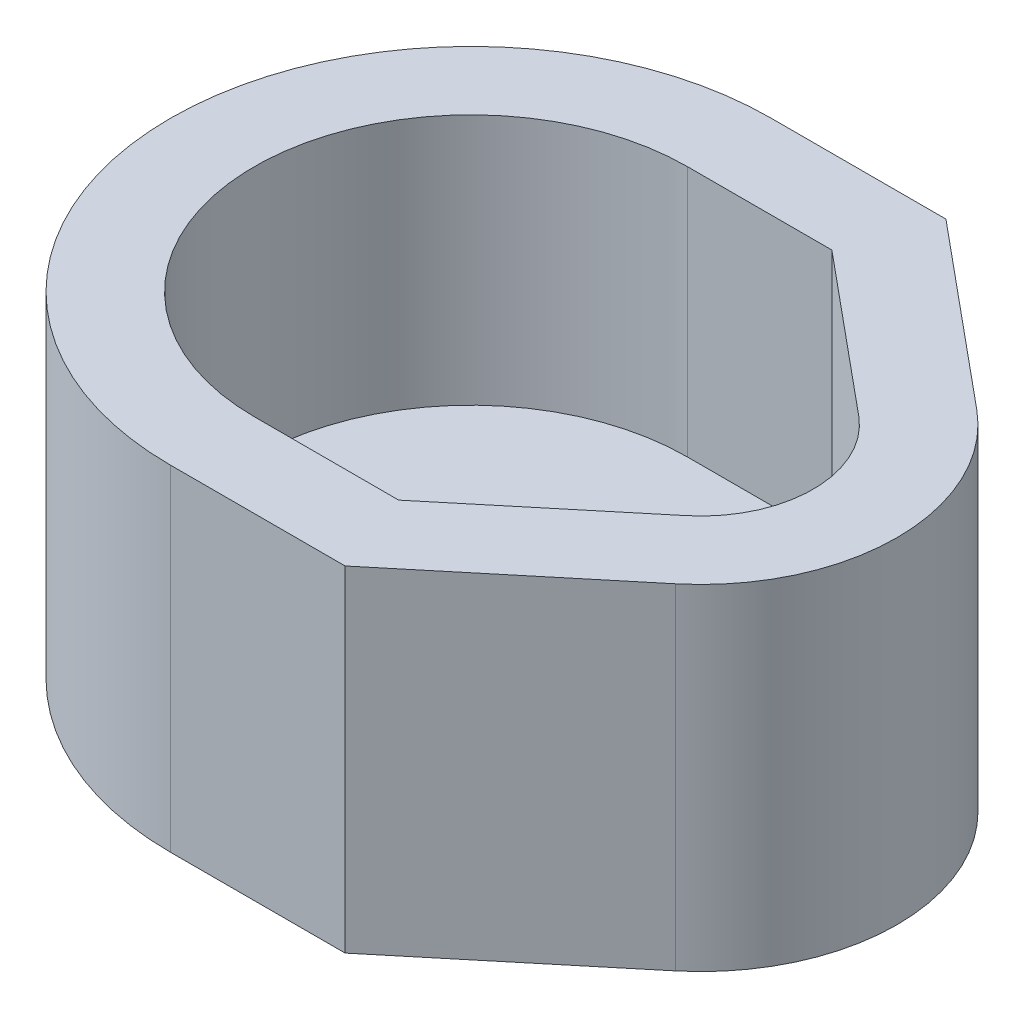
SolidWorks part; units mm, degrees
ref_plane "Front Plane" through (0, 0, 0) normal (0, 0, 1) x (1, 0, 0)
ref_plane "Top Plane" through (0, 0, 0) normal (0, 1, 0) x (1, 0, 0)
ref_plane "Right Plane" through (0, 0, 0) normal (1, 0, 0) x (0, 0, -1)
sketch "Sketch1" plane through (0, 0, 0) normal (0, 1, 0) x (1, 0, 0)
  line L9 (13.2334, 0) -> (26.9219, 11.3488)
  line L10 (26.9219, 34.168) -> (13.2334, 45.5168)
  line L12 (0, 0) -> (13.2334, 0)
  line L13 (0, 45.5168) -> (13.2334, 45.5168)
  arc A0 (26.9219, 11.3488) -> (26.9219, 34.168) centre (17.4625, 22.7584) ccw
  arc A1 (0, 45.5168) -> (0, 0) centre (0, 22.7584) ccw
  dimension "D1" = 22.7584
  dimension "D2" = 14.8209
  dimension "D3" = 13.2334
  dimension "D4" = 17.4625
extrude "Boss-Extrude1" add sketch "Sketch1" along normal blind 25.4
shell "Shell1" thickness 6.35
sketch "Sketch2" plane through (0, 6.35, 0) normal (0, 1, 0) x (1, 0, 0)
  circle A0 centre (0, 22.7584) radius 3.9815
  circle A1 centre (17.4625, 22.7584) radius 3.1877
  dimension "D1" = 7.9629
  dimension "D2" = 6.3754
extrude "Cut-Extrude1" cut sketch "Sketch2" against normal through all
equation "\"odpin\"= 0.417'OD of pinion gear, inches"
equation "\"pdpin\"= 0.375'pitch diameter of pinion, inches"
equation "\"odge\"= 1.042'od of big gear, inches"
equation "\"pdge\"= 1'pitch diameter gear, inches"
equation "\"wcent\"= ( ( \"pdpin\" + \"pdge\" ) / 2 )'length between centerline of shafts"
equation "\"clear\"= 1 / 8'clearance, per side"
equation "\"D1@Sketch1\"=(\"odge\"/2 + \"clear\" + \"wallt\")"
equation "\"wallt\"= 1 / 4'wall thickness"
equation "\"D2@Sketch1\"=(\"odpin\"/2 + \"clear\" + \"wallt\")"
equation "\"D3@Sketch1\"=(\"odge\"/2)"
equation "\"D4@Sketch1\"=\"wcent\""
equation "\"shaftL\"= 1'length of shaft"
equation "\"D1@Boss-Extrude1\"=\"shaftL\""
equation "\"D1@Shell1\"=\"wallt\""
equation "\"obear\"= 0.3135'diameter of output shaft"
equation "\"ibear\"= 0.251'diameter for bearing fit"
equation "\"D1@Sketch2\"=\"obear\""
equation "\"D2@Sketch2\"=\"ibear\""
